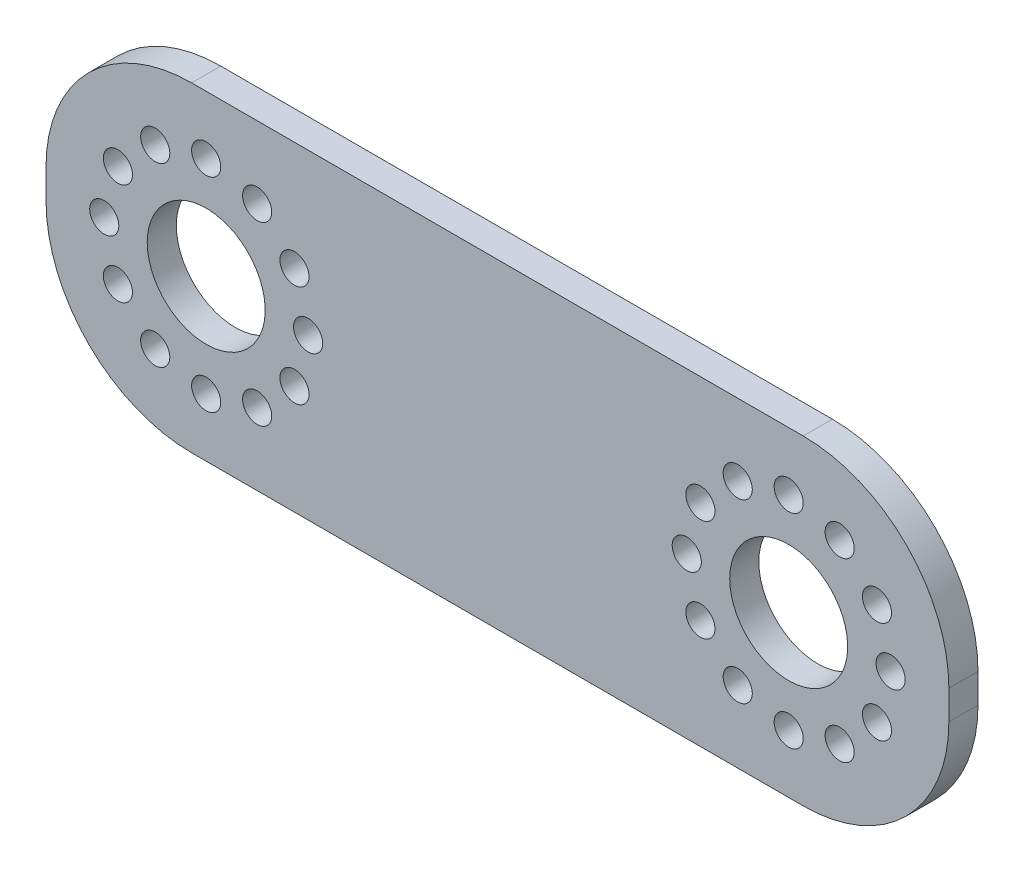
SolidWorks part; units mm, degrees
ref_plane "Plan de face" through (0, 0, 0) normal (0, 0, 1) x (1, 0, 0)
ref_plane "Plan de dessus" through (0, 0, 0) normal (0, 1, 0) x (1, 0, 0)
ref_plane "Plan de droite" through (0, 0, 0) normal (1, 0, 0) x (0, 0, -1)
sketch "Esquisse2" plane through (0, 0, 0) normal (0, 0, -1) x (-1, 0, 0)
  line L0 (-62, -11) -> (0, -11)
  line L2 (0, -11) -> (0, 11)
  line L3 (0, 11) -> (-62, 11)
  line L4 (-62, 11) -> (-62, -11)
  line L5 (-95.5557, 0) -> (0, 0) construction
  circle B0 centre (-11, 0) radius 4.05
  circle B1 centre (-4, 0) radius 1
  circle B2 centre (-4.9378, -3.5) radius 1
  circle B3 centre (-7.5, -6.0622) radius 1
  circle B4 centre (-11, -7) radius 1
  circle B5 centre (-14.5, -6.0622) radius 1
  circle B6 centre (-17.0622, -3.5) radius 1
  circle B7 centre (-18, 0) radius 1
  circle B8 centre (-17.0622, 3.5) radius 1
  circle B9 centre (-14.5, 6.0622) radius 1
  circle B10 centre (-11, 7) radius 1
  circle B11 centre (-7.5, 6.0622) radius 1
  circle B12 centre (-4.9378, 3.5) radius 1
  circle B13 centre (-51, 0) radius 4.05
  circle B14 centre (-44, 0) radius 1
  circle B15 centre (-44.9378, -3.5) radius 1
  circle B16 centre (-47.5, -6.0622) radius 1
  circle B17 centre (-51, -7) radius 1
  circle B18 centre (-54.5, -6.0622) radius 1
  circle B19 centre (-57.0622, -3.5) radius 1
  circle B20 centre (-58, 0) radius 1
  circle B21 centre (-57.0622, 3.5) radius 1
  circle B22 centre (-54.5, 6.0622) radius 1
  circle B23 centre (-51, 7) radius 1
  circle B24 centre (-47.5, 6.0622) radius 1
  circle B25 centre (-44.9378, 3.5) radius 1
  dimension "D1" = 22
  dimension "D2" = 11
  dimension "D3" = 11
  dimension "D4" = 40
sketch_block_instance "Block1-1"
sketch_block "Block1" parameters "D2"=2, "D3"=8.1, "D1"=7
sketch_block_instance "Block1-2"
extrude "Boss.-Extru.1" add sketch "Esquisse2" against normal blind 2
fillet "Congé1" radius 10 4 edges at (0, -11, 1) (0, 11, 1) (62, 11, 1) (62, -11, 1)
